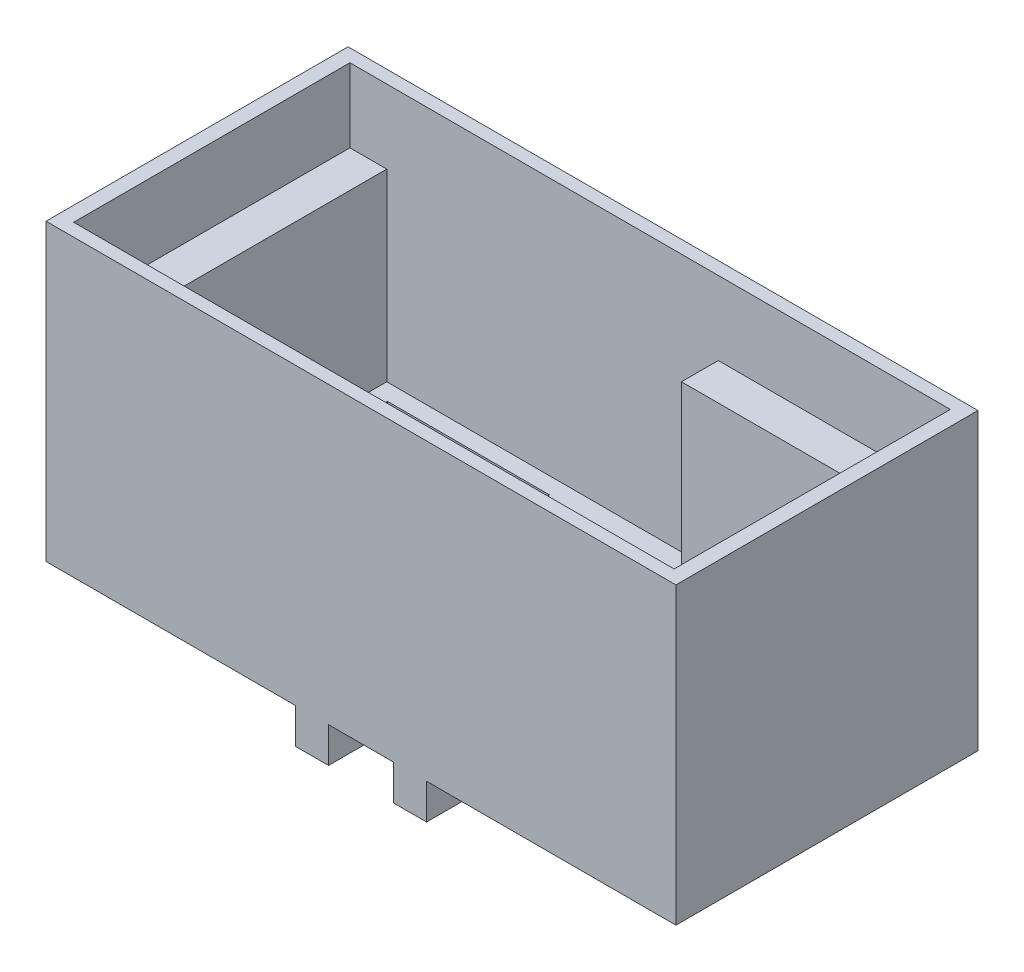
SolidWorks part; units mm, degrees
ref_plane "Front Plane" through (0, 0, 0) normal (0, 0, 1) x (1, 0, 0)
ref_plane "Top Plane" through (0, 0, 0) normal (0, 1, 0) x (1, 0, 0)
ref_plane "Right Plane" through (0, 0, 0) normal (1, 0, 0) x (0, 0, -1)
sketch "Sketch1" plane through (0, 0, 0) normal (0, 1, 0) x (1, 0, 0)
  line L1 (-42.75, -20.5) -> (42.75, -20.5)
  line L2 (-42.75, -20.5) -> (-42.75, 20.5)
  line L3 (-42.75, 20.5) -> (42.75, 20.5)
  line L4 (42.75, -20.5) -> (42.75, 20.5)
  line L5 (-42.75, -20.5) -> (42.75, 20.5) construction
  line L6 (-42.75, 20.5) -> (42.75, -20.5) construction
  point P0 (0, 0)
  dimension "D1" = 85.5
  dimension "D2" = 41
extrude "Boss-Extrude1" add sketch "Sketch1" along normal blind 40
sketch "Sketch2" plane through (0, 0, 0) normal (0, -1, 0) x (1, 0, 0)
  line L0 (-4.4, 0) -> (4.4, 0) construction
  line L1 (-42.75, 20.5) -> (42.75, 20.5) construction
  line L2 (-4.4, 20.5) -> (-8.9, 20.5)
  line L3 (-4.4, 20.5) -> (-4.4, -20.5)
  line L4 (-4.4, -20.5) -> (-8.9, -20.5)
  line L5 (-8.9, 20.5) -> (-8.9, -20.5)
  line L6 (42.75, -20.5) -> (-42.75, -20.5) construction
  line L8 (4.4, 20.5) -> (8.9, 20.5)
  line L9 (4.4, 20.5) -> (4.4, -20.5)
  line L10 (4.4, -20.5) -> (8.9, -20.5)
  line L11 (8.9, 20.5) -> (8.9, -20.5)
  point P3 (0, 0)
  point P4 (0, 0)
  point P17 (0, 0)
  point P18 (0, 0)
  dimension "D1" = 8.8
  dimension "D2" = 4.5
  dimension "D3" = 4.5
extrude "Boss-Extrude2" add sketch "Sketch2" along normal blind 4.8
sketch "Sketch5" plane through (0, 40, 0) normal (0, 1, 0) x (1, 0, 0)
  line L1 (-40.75, -18.75) -> (40.75, -18.75)
  line L2 (-40.75, -18.75) -> (-40.75, 18.75)
  line L3 (-40.75, 18.75) -> (40.75, 18.75)
  line L4 (40.75, -18.75) -> (40.75, 18.75)
  line L5 (-40.75, -18.75) -> (40.75, 18.75) construction
  line L6 (-40.75, 18.75) -> (40.75, -18.75) construction
  point P0 (0, 0)
  dimension "D1" = 37.5
  dimension "D2" = 81.5
extrude "Cut-Extrude1" cut sketch "Sketch5" against normal blind 10
sketch "Sketch6" plane through (0, 30, 0) normal (0, 1, 0) x (1, 0, 0)
  line L0 (-40.75, 18.75) -> (-35.75, 18.75) construction
  line L1 (40.75, 18.75) -> (-40.75, 18.75) construction
  line L2 (40.75, -18.75) -> (35.75, -18.75) construction
  line L3 (-35.75, 18.75) -> (9.25, 18.75)
  line L4 (-35.75, 18.75) -> (-35.75, 13.75)
  line L5 (-35.75, 13.75) -> (9.25, 13.75)
  line L6 (9.25, 18.75) -> (9.25, 13.75)
  line L7 (-40.75, -18.75) -> (40.75, -18.75) construction
  line L9 (35.75, -18.75) -> (-9.25, -18.75)
  line L10 (35.75, -18.75) -> (35.75, -13.75)
  line L11 (35.75, -13.75) -> (-9.25, -13.75)
  line L12 (-9.25, -18.75) -> (-9.25, -13.75)
  dimension "D1" = 5
  dimension "D2" = 5
  dimension "D3" = 45
  dimension "D4" = 5
  dimension "D5" = 45
  dimension "D6" = 5
extrude "Cut-Extrude2" cut sketch "Sketch6" against normal blind 25
sketch "Sketch7" plane through (0, 30, 0) normal (0, 1, 0) x (1, 0, 0)
  line L1 (-35.75, 13.75) -> (35.75, 13.75)
  line L2 (-35.75, 13.75) -> (-35.75, -13.75)
  line L3 (-35.75, -13.75) -> (35.75, -13.75)
  line L4 (35.75, 13.75) -> (35.75, -13.75)
extrude "Cut-Extrude3" cut sketch "Sketch7" against normal blind 25
sketch "Sketch10" plane through (0, 5, 0) normal (0, 1, 0) x (1, 0, 0)
  line L0 (-35.75, 18.75) -> (-8.8761, 18.75) construction
  line L1 (40.75, 18.75) -> (-40.75, 18.75) construction
  line L2 (-22.313, 18.75) -> (-22.5, -13.75) construction
  line L3 (-35.75, -13.75) -> (-9.25, -13.75) construction
  line L4 (35.75, -18.75) -> (8.9, -18.75) construction
  line L5 (-33.4065, -11.5) -> (-11.4065, -11.5)
  line L6 (-33.4065, -11.5) -> (-33.4065, 16.5)
  line L7 (-33.4065, 16.5) -> (-11.4065, 16.5)
  line L8 (-11.4065, -11.5) -> (-11.4065, 16.5)
  line L9 (-33.4065, -11.5) -> (-11.4065, 16.5) construction
  line L10 (-33.4065, 16.5) -> (-11.4065, -11.5) construction
  line L11 (-40.75, -18.75) -> (40.75, -18.75) construction
  line L12 (8.9, 20.5) -> (8.9, -20.5) construction
  line L13 (22.5, 13.75) -> (22.325, -18.75) construction
  line L14 (35.75, 13.75) -> (9.25, 13.75) construction
  line L16 (11.4125, -16.5) -> (33.4125, -16.5)
  line L17 (11.4125, -16.5) -> (11.4125, 11.5)
  line L18 (11.4125, 11.5) -> (33.4125, 11.5)
  line L19 (33.4125, -16.5) -> (33.4125, 11.5)
  line L20 (11.4125, -16.5) -> (33.4125, 11.5) construction
  line L21 (11.4125, 11.5) -> (33.4125, -16.5) construction
  point P9 (-22.4065, 2.5)
  point P25 (22.4125, -2.5)
  dimension "D1" = 22
  dimension "D2" = 28
  dimension "D3" = 22
  dimension "D4" = 28
extrude "Cut-Extrude4" cut sketch "Sketch10" against normal up to next
